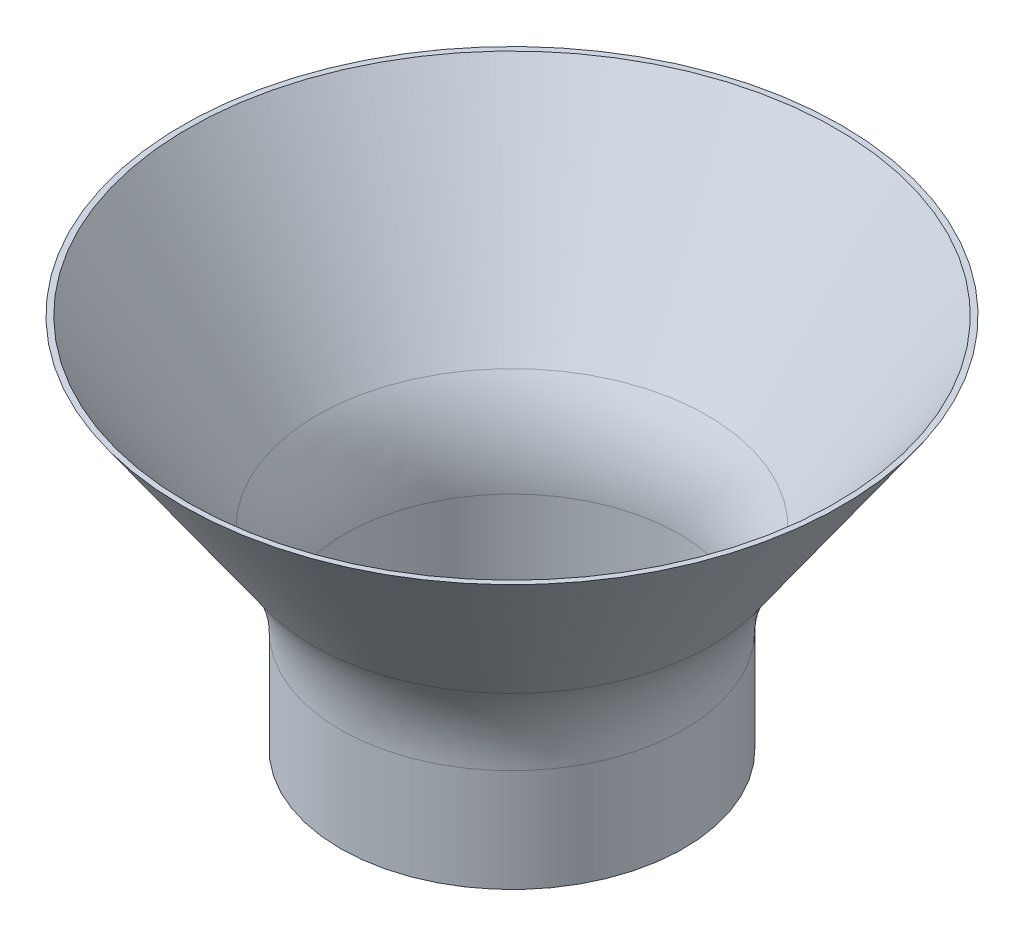
SolidWorks part; units mm, degrees
ref_plane "Front Plane" through (0, 0, 0) normal (0, 0, 1) x (1, 0, 0)
ref_plane "Top Plane" through (0, 0, 0) normal (0, 1, 0) x (1, 0, 0)
ref_plane "Right Plane" through (0, 0, 0) normal (1, 0, 0) x (0, 0, -1)
sketch "Sketch1" plane through (0, 0, 0) normal (0, 1, 0) x (1, 0, 0)
  circle A0 centre (0, 0) radius 34.925 construction
  circle A1 centre (0, 0) radius 30.0482 construction
  circle A2 centre (0, 0) radius 29.0449
  dimension "D1" = 69.85
  dimension "D2" = 60.0964
  dimension "D3" = 58.0898
extrude "Boss-Extrude3" add sketch "Sketch1" along normal blind 25.4
sketch "Sketch6" plane through (0, 25.4, 0) normal (0, 1, 0) x (1, 0, 0)
  circle A1 centre (0, 0) radius 29.0449
  circle A2 centre (0, 0) radius 29.0449
  dimension "D1" = 0
extrude "Boss-Extrude4" add sketch "Sketch6" along normal blind 38.1 draft 35 draft outward yes
fillet "Fillet1" radius 25.4 1 edges at (0, 25.4, 29.0449)
shell "Shell2" thickness 0.762
